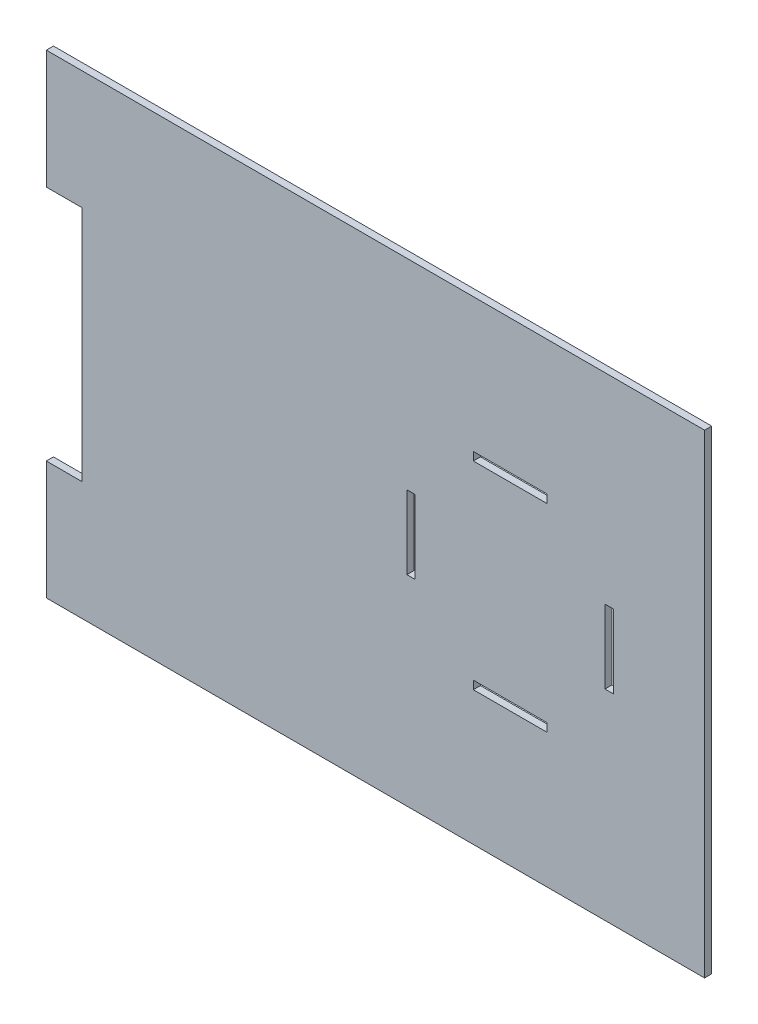
SolidWorks part; units mm, degrees
ref_plane "Plano frontal" through (0, 0, 0) normal (0, 0, 1) x (1, 0, 0)
ref_plane "Plano superior" through (0, 0, 0) normal (0, 1, 0) x (1, 0, 0)
ref_plane "Plano direito" through (0, 0, 0) normal (1, 0, 0) x (0, 0, -1)
sketch "Esboço1" plane through (0, 0, 0) normal (0, 0, 1) x (1, 0, 0)
  line L1 (-277.5, -100) -> (277.5, -100)
  line L2 (-277.5, -100) -> (-277.5, 100)
  line L3 (-277.5, 100) -> (277.5, 100)
  line L4 (277.5, -100) -> (277.5, 100)
  line L5 (-277.5, -100) -> (277.5, 100) construction
  line L6 (-277.5, 100) -> (277.5, -100) construction
  point P0 (0, 0)
  dimension "D1" = 555
  dimension "D2" = 200
extrude "Ressalto-extrusão1" add sketch "Esboço1" along normal blind 3
sketch "Esboço2" plane through (0, 0, 3) normal (0, 0, 1) x (1, 0, 0)
  line L0 (-277.5, 0) -> (277.5, 0) construction
  line L1 (-277.5, 100) -> (-277.5, -100) construction
  line L2 (277.5, -100) -> (277.5, 100) construction
  line L3 (0, 100) -> (0, -100) construction
  line L4 (277.5, 100) -> (-277.5, 100) construction
  line L5 (-277.5, -100) -> (277.5, -100) construction
  line L6 (-195.5, 100) -> (-195.5, -100) construction
  line L11 (239, 15.5) -> (235.5, 15.5)
  line L12 (235.5, -15.5) -> (235.5, 15.5)
  line L13 (-155.5, -15.5) -> (-152, -15.5)
  line L14 (-155.5, -15.5) -> (-155.5, 15.5)
  line L15 (-155.5, 15.5) -> (-152, 15.5)
  line L16 (-152, -15.5) -> (-152, 15.5)
  line L17 (-155.5, -15.5) -> (-152, 15.5) construction
  line L18 (-155.5, 15.5) -> (-152, -15.5) construction
  line L19 (-239, -15.5) -> (-235.5, -15.5)
  line L20 (-239, -15.5) -> (-239, 15.5)
  line L21 (-239, 15.5) -> (-235.5, 15.5)
  line L22 (-235.5, -15.5) -> (-235.5, 15.5)
  line L23 (-239, -15.5) -> (-235.5, 15.5) construction
  line L24 (-239, 15.5) -> (-235.5, -15.5) construction
  line L25 (-211, 40) -> (-180, 40)
  line L26 (-211, -43.5) -> (-180, -43.5)
  line L27 (-211, -43.5) -> (-211, -40)
  line L28 (-211, -40) -> (-180, -40)
  line L29 (-180, -43.5) -> (-180, -40)
  line L30 (-211, -43.5) -> (-180, -40) construction
  line L31 (-211, -40) -> (-180, -43.5) construction
  line L32 (-180, 43.5) -> (-180, 40)
  line L33 (-211, 43.5) -> (-180, 43.5)
  line L34 (-211, 43.5) -> (-211, 40)
  line L35 (239, -15.5) -> (235.5, -15.5)
  line L36 (239, -15.5) -> (239, 15.5)
  line L37 (155.5, 15.5) -> (152, 15.5)
  line L38 (152, -15.5) -> (152, 15.5)
  line L39 (155.5, -15.5) -> (152, -15.5)
  line L40 (155.5, -15.5) -> (155.5, 15.5)
  line L41 (211, -40) -> (180, -40)
  line L42 (180, -43.5) -> (180, -40)
  line L43 (211, -43.5) -> (180, -43.5)
  line L44 (211, -43.5) -> (211, -40)
  line L45 (211, 43.5) -> (211, 40)
  line L46 (211, 43.5) -> (180, 43.5)
  line L47 (180, 43.5) -> (180, 40)
  line L48 (211, 40) -> (180, 40)
  point P17 (-153.75, 0)
  point P22 (-237.25, 0)
  point P29 (-195.5, -41.75)
  dimension "D3" = 3.5
  dimension "D4" = 31
  dimension "D6" = 122
  dimension "D7" = 31
  dimension "D8" = 3.5
  dimension "D9" = 80
  dimension "D10" = 31
  dimension "D11" = 3.5
  dimension "D12" = 80
  dimension "D13" = 40
extrude "Corte-extrusão1" cut sketch "Esboço2" against normal through all
sketch "Esboço3" plane through (0, 0, 3) normal (0, 0, 1) x (1, 0, 0)
  line L0 (0, 100) -> (0, 50)
  line L1 (277.5, 100) -> (-277.5, 100) construction
  line L2 (-277.5, -100) -> (277.5, -100) construction
  line L3 (0, -50) -> (15, -50)
  line L4 (15, -50) -> (15, 50)
  line L5 (15, 50) -> (0, 50)
  line L6 (0, -50) -> (0, -100)
  line L11 (277.5, -100) -> (277.5, 100)
  line L12 (277.5, 100) -> (-277.5, 100)
  line L13 (-277.5, 100) -> (-277.5, -100)
  line L14 (-277.5, -100) -> (277.5, -100)
  line L15 (277.5, -100) -> (277.5, 100)
  line L16 (277.5, 100) -> (0, 100)
  line L18 (0, -100) -> (277.5, -100)
  dimension "D1" = 100
  dimension "D2" = 15
  dimension "D3" = 50
  dimension "D4" = 0
extrude "Corte-extrusão3" cut sketch "Esboço3" against normal through all flip side to cut
